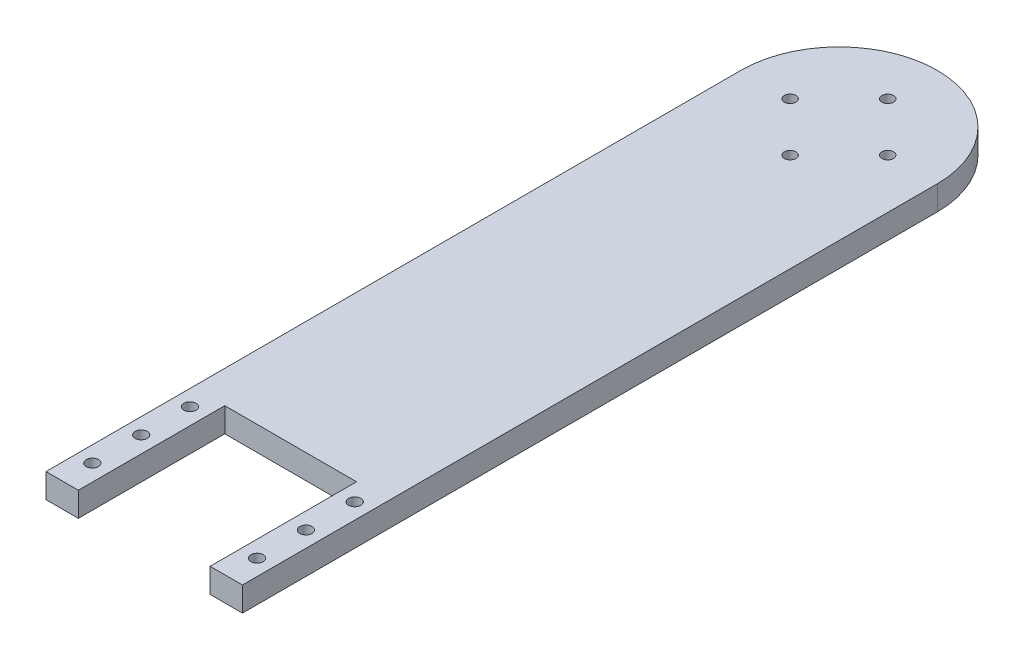
SolidWorks part; units mm, degrees
ref_plane "Plan de face" through (0, 0, 0) normal (0, 0, 1) x (1, 0, 0)
ref_plane "Plan de dessus" through (0, 0, 0) normal (0, 1, 0) x (1, 0, 0)
ref_plane "Plan de droite" through (0, 0, 0) normal (1, 0, 0) x (0, 0, -1)
sketch "Esquisse1" plane through (0, 0, 0) normal (0, 1, 0) x (1, 0, 0)
  line L0 (0, 0) -> (16.1, 0) construction
  line L1 (16.1, 0) -> (-16.1, 0) construction
  line L2 (0, -16.1) -> (0, 16.1) construction
  line L3 (0, 16.1) -> (-16.1, 16.1) construction
  line L4 (-16.1, 16.1) -> (-16.1, -113.9) construction
  line L5 (-16.1, 0) -> (-16.1, -113.9)
  line L6 (-16.1, -113.9) -> (16.1, -113.9)
  line L7 (16.1, -113.9) -> (16.1, 0)
  arc A0 (16.1, 0) -> (-16.1, 0) centre (0, 0) ccw
  dimension "D1" = 32.2
  dimension "D2" = 130
extrude "Boss.-Extru.1" add sketch "Esquisse1" along normal blind 4
sketch "Esquisse2" plane through (0, 4, 0) normal (0, 1, 0) x (1, 0, 0)
  line L0 (16.1, -113.9) -> (16.1, -108.9) construction
  line L1 (16.1, -113.9) -> (16.1, 0) construction
  line L2 (0, -113.9) -> (0, -108.9)
  line L3 (0, 16.1) -> (0, 0) construction
  line L4 (0, 0) -> (0, -30.9342) construction
  line L5 (0, 16.1) -> (0, 14.1) construction
  line L6 (-11, 0) -> (16.1, 0) construction
  line L7 (16.1, 0) -> (-16.1, 0) construction
  line L8 (0, -14.1) -> (11, -14.1) construction
  line L9 (0, -14.1) -> (-11, -14.1) construction
  line L10 (-11, -14.1) -> (-11, 0) construction
  line L11 (11, -14.1) -> (11, 0) construction
  line L12 (-16.1, -113.9) -> (16.1, -113.9) construction
  line L13 (13.5, -107.9) -> (13.5, -101.9)
  line L14 (-12.5, -108.9) -> (12.5, -108.9)
  line L15 (12.5, -108.9) -> (13.5, -108.9)
  line L16 (-12.5, -108.9) -> (-13.5, -108.9)
  line L17 (-13.5, -107.9) -> (-13.5, -101.9)
  line L18 (13.5, -101.9) -> (13.5, -100.9)
  line L19 (-13.5, -101.9) -> (-13.5, -100.9)
  line L20 (-13.5, -100.9) -> (-13.5, -99.9)
  line L21 (13.5, -100.9) -> (13.5, -99.9)
  line L22 (-13.5, -101.9) -> (13.5, -101.9)
  line L23 (-13.5, -99.9) -> (-13.5, -93.9)
  line L24 (13.5, -99.9) -> (13.5, -93.9)
  line L25 (13.5, -93.9) -> (13.5, -92.9)
  line L26 (0, 16.1) -> (0, 14.1) construction
  line L27 (0, 14.1) -> (0, 11.1) construction
  line L28 (0, 14.1) -> (0, 11.1) construction
  line L29 (0, 11.1) -> (0, 12.6) construction
  line L30 (-13.5, -93.9) -> (-13.5, -92.9)
  arc A0 (16.1, 0) -> (-16.1, 0) centre (0, 0) ccw construction
  circle A11 centre (7.9751, -0.0023) radius 0.955
  circle A12 centre (-8.0249, -0.0023) radius 0.955
  circle A13 centre (-0.0249, -8.0023) radius 0.955
  circle A14 centre (-0.0249, 7.9977) radius 0.955
  circle A15 centre (-13.5, -108.9) radius 1
  circle A16 centre (13.5, -108.9) radius 1
  circle A17 centre (-13.5, -100.9) radius 1
  circle A18 centre (13.5, -100.9) radius 1
  circle A19 centre (-13.5, -92.9) radius 1
  circle A20 centre (13.5, -92.9) radius 1
  point P36 (0, -108.9)
  dimension "D4" = 2
  dimension "D5" = 1
  dimension "D8" = 1
  dimension "D10" = 6
  dimension "D1" = 5
  dimension "D2" = 25
  dimension "D3" = 3
  dimension "D6" = 11
  dimension "D7" = 11
  dimension "D9" = 6
  dimension "D11" = 6
  dimension "D12" = 6
extrude "Enlèv. mat.-Extru.1" cut sketch "Esquisse2" against normal blind 4 contours A15 | A17 | A19 | A20 | A18 | A16 | A12 | A13 | A11 | A14
sketch "Esquisse4" plane through (0, 4, 0) normal (0, 1, 0) x (1, 0, 0)
  line L0 (-8.684, -113.9) -> (9.316, -113.9)
  line L1 (-16.1, -113.9) -> (16.1, -113.9) construction
  line L2 (-8.684, -113.9) -> (-8.684, -89.9)
  line L3 (-8.684, -89.9) -> (9.316, -89.9)
  line L4 (9.316, -89.9) -> (9.316, -113.9)
  point P5 (0.316, -113.9)
extrude "Enlèv. mat.-Extru.2" cut sketch "Esquisse4" against normal blind 10 contours L4 L0 L2 L3
sketch "Esquisse5" plane through (0, 4, 0) normal (0, 1, 0) x (1, 0, 0)
  line L0 (-16.1, -113.9) -> (-10.8, -113.9)
  line L1 (-16.1, -113.9) -> (-8.684, -113.9) construction
  line L2 (-10.8, -113.9) -> (-8.684, -113.9)
  line L3 (-8.684, -113.9) -> (-8.684, -89.9)
  line L4 (-8.684, -89.9) -> (-10.8, -89.9)
  line L5 (-10.8, -89.9) -> (-10.8, -113.9)
  line L6 (16.1, -113.9) -> (10.8, -113.9)
  line L7 (9.316, -113.9) -> (16.1, -113.9) construction
  line L8 (10.8, -113.9) -> (10.8, -89.9)
  line L9 (10.8, -89.9) -> (9.316, -89.9)
  line L10 (9.316, -89.9) -> (9.316, -113.9)
  line L11 (9.316, -113.9) -> (10.8, -113.9)
  line M17 (-16.1, -113.9) -> (-8.684, -113.9)
  line M18 (-8.684, -113.9) -> (-8.684, -89.9)
extrude "Enlèv. mat.-Extru.3" cut sketch "Esquisse5" against normal blind 10 contours L4 L5 M17 M18 | L8 L9 L10 L11
